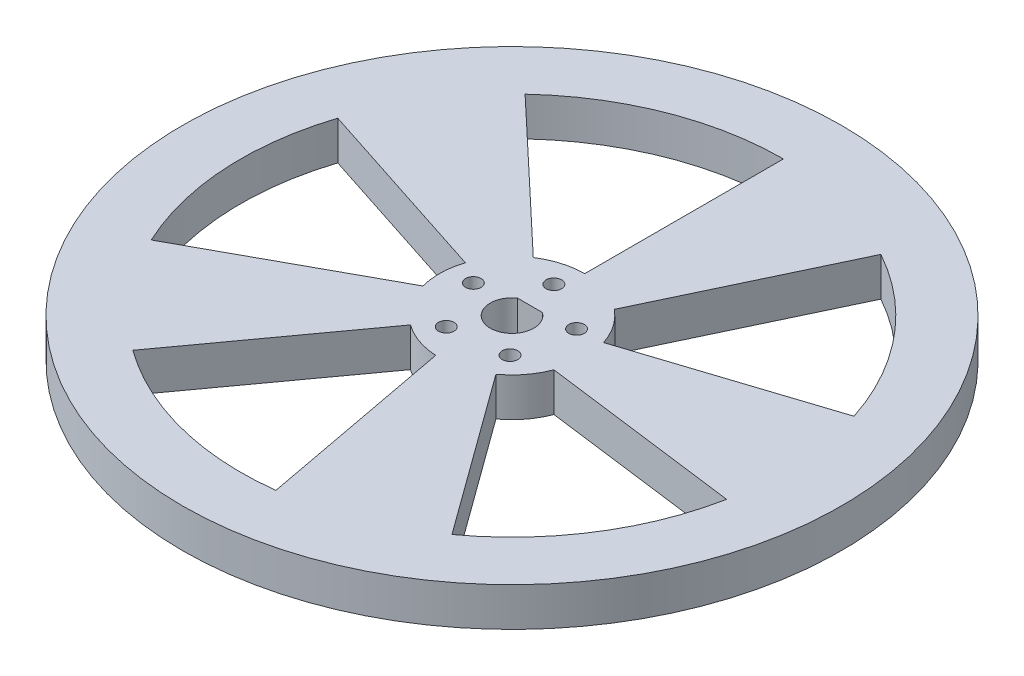
SolidWorks part; units mm, degrees
ref_plane "Front Plane" through (0, 0, 0) normal (0, 0, 1) x (1, 0, 0)
ref_plane "Top Plane" through (0, 0, 0) normal (0, 1, 0) x (1, 0, 0)
ref_plane "Right Plane" through (0, 0, 0) normal (1, 0, 0) x (0, 0, -1)
sketch "Sketch2" plane through (0, 0, 0) normal (0, 1, 0) x (1, 0, 0)
  circle A0 centre (0, 0) radius 43.18
  dimension "D1" = 86.36
extrude "Boss-Extrude1" add sketch "Sketch2" along normal blind 5.08
sketch "Sketch3" plane through (0, 5.08, 0) normal (0, 1, 0) x (1, 0, 0)
  line L0 (-1.6264, 2.3495) -> (1.6264, 2.3495)
  circle A0 centre (0, 0) radius 2.8575
  point P5 (0, -2.8575)
  dimension "D1" = 5.715
  dimension "D2" = 5.207
extrude "Cut-Extrude1" cut sketch "Sketch3" against normal through all contours L0 A0
sketch "Sketch5" plane through (0, 5.08, 0) normal (0, 1, 0) x (1, 0, 0)
  line L0 (-33.8196, 10.9886) -> (-9.0588, 2.9434)
  line L1 (0, 35.56) -> (-33.8196, 10.9886) construction
  line L2 (-33.8196, 10.9886) -> (-20.9016, -28.7686) construction
  line L3 (-20.9016, -28.7686) -> (20.9016, -28.7686) construction
  line L4 (20.9016, -28.7686) -> (33.8196, 10.9886) construction
  line L5 (33.8196, 10.9886) -> (0, 35.56) construction
  line L6 (0, 9.525) -> (-9.0588, 2.9434) construction
  line L7 (-9.0588, 2.9434) -> (-5.5987, -7.7059) construction
  line L8 (-5.5987, -7.7059) -> (5.5987, -7.7059) construction
  line L9 (5.5987, -7.7059) -> (9.0588, 2.9434) construction
  line L10 (9.0588, 2.9434) -> (0, 9.525) construction
  line L11 (0, 35.56) -> (0, 9.525)
  line L12 (33.8196, 10.9886) -> (9.0588, 2.9434)
  line L13 (20.9016, -28.7686) -> (5.5987, -7.7059)
  line L14 (-20.9016, -28.7686) -> (-5.5987, -7.7059)
  line L15 (-24.2723, 25.9879) -> (-5.1957, 7.9831)
  line L16 (17.2154, 31.115) -> (5.9868, 7.4083)
  line L17 (34.9055, -6.7914) -> (8.895, -3.4066)
  line L18 (4.3614, -35.2915) -> (-0.4889, -9.5124)
  line L19 (-32.2165, -15.0536) -> (-9.198, -2.4745)
  circle A0 centre (0, 0) radius 35.56
  circle A1 centre (0, 0) radius 28.7686 construction
  arc A2 (0, 35.56) -> (17.2154, 31.115) centre (0, 0) cw
  arc A3 (33.8196, 10.9886) -> (34.9055, -6.7914) centre (0, 0) cw
  arc A4 (20.9016, -28.7686) -> (4.3614, -35.2915) centre (0, 0) cw
  arc A5 (-20.9016, -28.7686) -> (-32.2165, -15.0536) centre (0, 0) cw
  arc A6 (-33.8196, 10.9886) -> (-24.2723, 25.9879) centre (0, 0) cw
  circle A7 centre (0, 0) radius 9.525
  circle A8 centre (0, 0) radius 7.7059 construction
  arc A9 (-9.0588, 2.9434) -> (-5.1957, 7.9831) centre (0, 0) cw
  arc A10 (0, 9.525) -> (5.9868, 7.4083) centre (0, 0) cw
  arc A11 (9.0588, 2.9434) -> (8.895, -3.4066) centre (0, 0) cw
  arc A12 (5.5987, -7.7059) -> (-0.4889, -9.5124) centre (0, 0) cw
  arc A13 (-5.5987, -7.7059) -> (-9.198, -2.4745) centre (0, 0) cw
  dimension "D1" = 71.12
  dimension "D7" = 19.05
  dimension "D10" = 6.35
  dimension "D2" = 17.78
  dimension "D3" = 17.78
  dimension "D4" = 17.78
  dimension "D5" = 17.78
  dimension "D6" = 17.78
  dimension "D8" = 6.35
  dimension "D9" = 6.35
  dimension "D11" = 6.35
  dimension "D12" = 6.35
extrude "Cut-Extrude2" cut sketch "Sketch5" against normal through all contours A7 L0 A0 L19 | A7 L14 A0 L18 | A7 L13 A0 L17 | A7 L12 A0 L16 | A7 L11 A0 L15
sketch "Sketch6" plane through (0, 5.08, 0) normal (0, 1, 0) x (1, 0, 0)
  line L1 (5.7385, 2.7189) -> (-0.8126, 6.2978) construction
  line L2 (-0.8126, 6.2978) -> (-6.2407, 1.1733) construction
  line L3 (-6.2407, 1.1733) -> (-3.0444, -5.5726) construction
  line L4 (-3.0444, -5.5726) -> (4.3591, -4.6174) construction
  line L5 (4.3591, -4.6174) -> (5.7385, 2.7189) construction
  circle A0 centre (0, 0) radius 5.1373 construction
  circle A1 centre (5.7385, 2.7189) radius 1.016
  circle A2 centre (4.3591, -4.6174) radius 1.016
  circle A4 centre (-6.2407, 1.1733) radius 1.016
  circle A5 centre (-0.8126, 6.2978) radius 1.016
  circle A6 centre (-3.0444, -5.5726) radius 1.016
  dimension "D2" = 2.032
  dimension "D3" = 2.032
  dimension "D4" = 2.032
  dimension "D5" = 2.032
  dimension "D6" = 2.032
  dimension "D1" = 6.35
extrude "Cut-Extrude3" cut sketch "Sketch6" against normal through all
equation "\"MDF\"= .2"
equation "\"Foamcore\"= .1"
equation "\"GMaterial\"= \"MDF\""
equation "\"CutDistance\" = .1"
equation "\"D1@Boss-Extrude1\"=\"GMaterial\""
